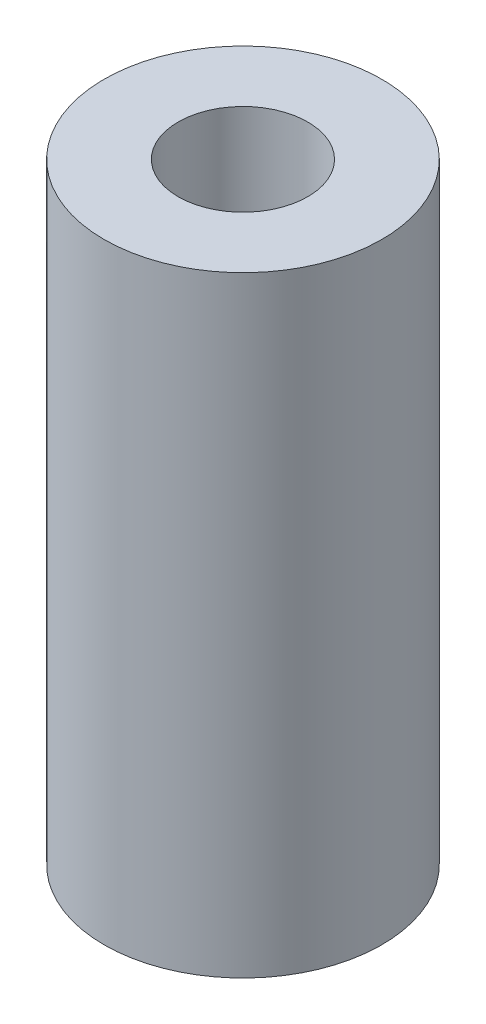
SolidWorks part; units mm, degrees
ref_plane "前视基准面" through (0, 0, 0) normal (0, 0, 1) x (1, 0, 0)
ref_plane "上视基准面" through (0, 0, 0) normal (0, 1, 0) x (1, 0, 0)
ref_plane "右视基准面" through (0, 0, 0) normal (1, 0, 0) x (0, 0, -1)
other "Configuration Table"
sketch "草图2" plane through (0, 0, 0) normal (0, 1, 0) x (1, 0, 0)
  circle A18 centre (0, 0) radius 3.75
  circle A19 centre (0, 0) radius 1.75
  dimension "D1" = 3.5
  dimension "D2" = 2
extrude "凸台-拉伸1" add sketch "草图2" along normal blind 16.5
